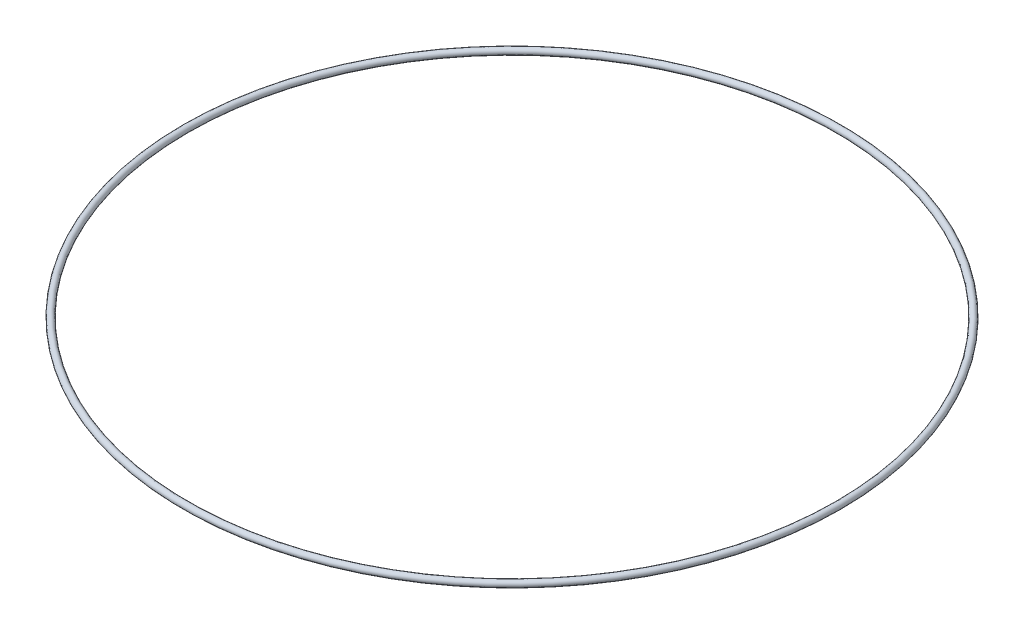
SolidWorks part; units mm, degrees
ref_plane "Front Plane" through (0, 0, 0) normal (0, 0, 1) x (1, 0, 0)
ref_plane "Top Plane" through (0, 0, 0) normal (0, 1, 0) x (1, 0, 0)
ref_plane "Right Plane" through (0, 0, 0) normal (1, 0, 0) x (0, 0, -1)
sketch "Sketch1" plane through (0, 0, 0) normal (0, 1, 0) x (1, 0, 0)
  circle A0 centre (0, 0) radius 127
sketch "Sketch2" plane through (0, 0, 0) normal (0, 0, 1) x (1, 0, 0)
  line L0 (127, 0) -> (-127, 0) construction
  circle A0 centre (-127, 0) radius 1.27
sweep "Sweep1" add profiles "Sketch2" path "Sketch1"
